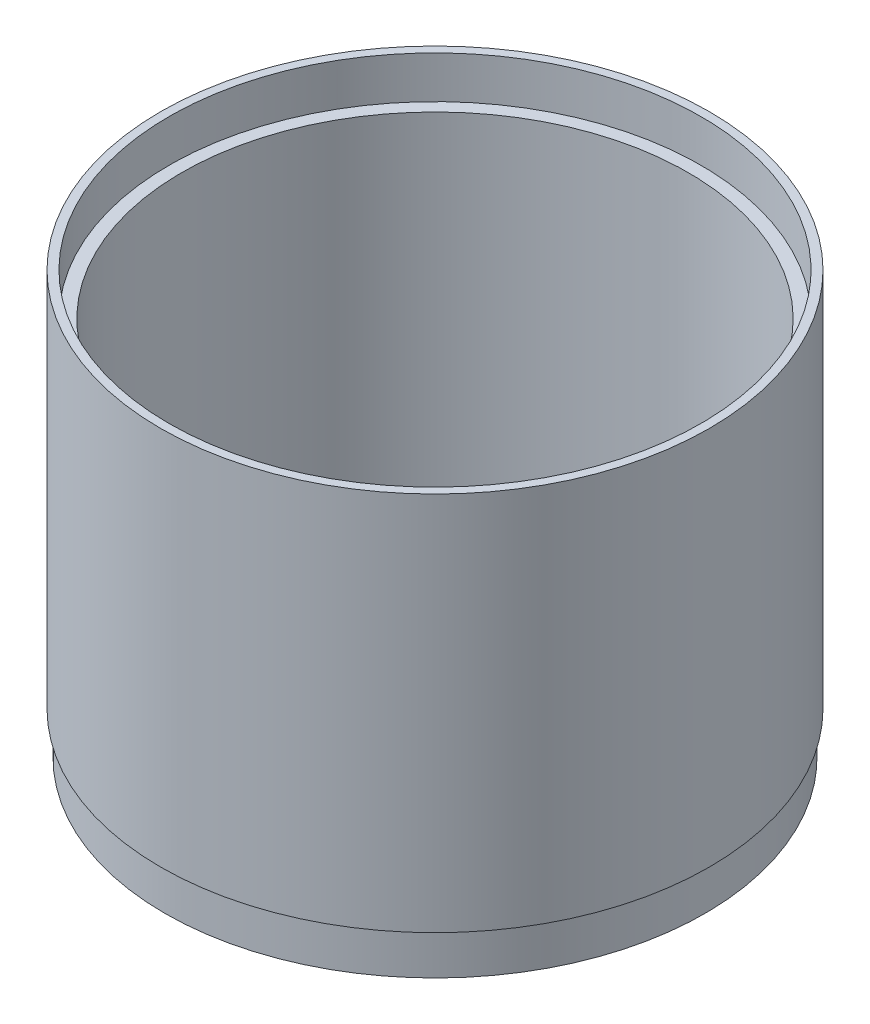
SolidWorks part; units mm, degrees
material "HYPALON"
ref_plane "Front Plane" through (0, 0, 0) normal (0, 0, 1) x (1, 0, 0)
ref_plane "Top Plane" through (0, 0, 0) normal (0, 1, 0) x (1, 0, 0)
ref_plane "Right Plane" through (0, 0, 0) normal (1, 0, 0) x (0, 0, -1)
sketch "Szkic1" plane through (0, 0, 0) normal (0, 0, 1) x (1, 0, 0)
  line L0 (-64, 0) -> (0, 0)
  line L1 (-64, 0) -> (-60, 0)
  line L2 (-64, 0) -> (-64, 10)
  line L3 (-64, 10) -> (-65, 10)
  line L4 (-65, 10) -> (-65, 28.5618)
  line L5 (-60, 0) -> (-60, 90)
  line L6 (-60, 90) -> (-63, 90)
  line L7 (-63, 90) -> (-63, 100)
  line L8 (-63, 100) -> (-65, 100)
  line L9 (-65, 100) -> (-65, 28.5618)
  line L10 (0, 35.541) -> (0, 0)
  dimension "D1" = 65
  dimension "D2" = 10
  dimension "D3" = 1
  dimension "D4" = 10
  dimension "D5" = 2
  dimension "D6" = 5
  dimension "D7" = 60
  dimension "D8" = 90
revolve "Obrót1" add sketch "Szkic1" angle 360 about L10
